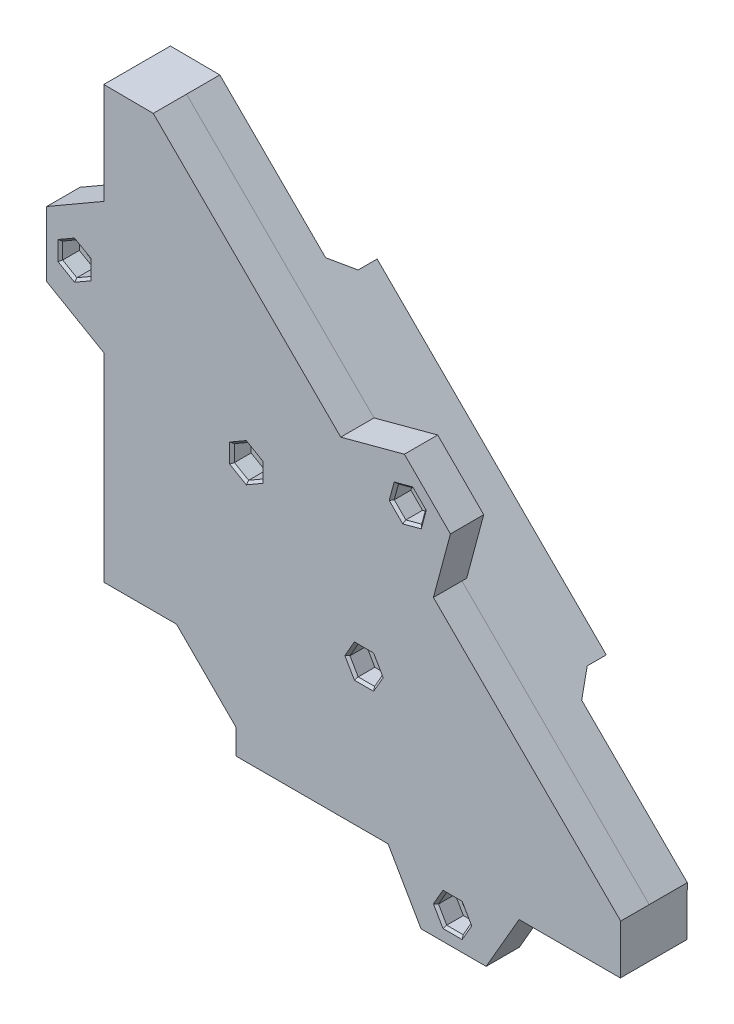
SolidWorks part; units mm, degrees
ref_plane "Front Plane" through (0, 0, 0) normal (0, 0, 1) x (1, 0, 0)
ref_plane "Top Plane" through (0, 0, 0) normal (0, 1, 0) x (1, 0, 0)
ref_plane "Right Plane" through (0, 0, 0) normal (1, 0, 0) x (0, 0, -1)
sketch "Sketch1" plane through (0, 0, 0) normal (0, 0, 1) x (1, 0, 0)
  line L0 (-86.0013, 66.2134) -> (-46.6464, 27) construction
  line L1 (-46.6464, 27) -> (-46.7159, 16.3926) construction
  line L2 (-46.7159, 16.3926) -> (-68.069, 16.3926) construction
  line L3 (-68.069, 16.3926) -> (-74.9972, 4.3926) construction
  line L4 (-74.9972, 4.3926) -> (-88.8536, 4.3926) construction
  line L5 (-88.8536, 4.3926) -> (-95.7818, 16.3926) construction
  line L6 (-95.7818, 16.3926) -> (-127.85, 16.3926) construction
  line L7 (-127.85, 16.3926) -> (-127.85, 21.7674) construction
  line L8 (-127.85, 21.7674) -> (-140.2326, 34.15) construction
  line L9 (-140.2326, 34.15) -> (-155.6074, 34.15) construction
  line L11 (-155.6074, 125.0695) -> (-145, 125) construction
  line L12 (-145, 125) -> (-105.6047, 85.7815) construction
  line L13 (-105.6047, 85.7815) -> (-92.2204, 89.3678) construction
  line L14 (-92.2204, 89.3678) -> (-82.4224, 79.5698) construction
  line L15 (-82.4224, 79.5698) -> (-86.0013, 66.2134) construction
  line L16 (-155.6074, 125.0695) -> (-155.6074, 103.716) construction
  line L17 (-155.6074, 103.716) -> (-167.6074, 96.7878) construction
  line L18 (-167.6074, 96.7878) -> (-167.6074, 82.9314) construction
  line L19 (-167.6074, 82.9314) -> (-155.6074, 76.0032) construction
  line L20 (-155.6074, 76.0032) -> (-155.6074, 34.15) construction
  line L21 (-86.1686, 66.1684) -> (-46.7969, 26.9381)
  line L22 (-46.7969, 26.9381) -> (-46.8649, 16.5426)
  line L23 (-46.8649, 16.5426) -> (-68.1556, 16.5426)
  line L24 (-68.1556, 16.5426) -> (-75.0838, 4.5426)
  line L25 (-75.0838, 4.5426) -> (-88.767, 4.5426)
  line L26 (-88.767, 4.5426) -> (-95.6952, 16.5426)
  line L27 (-95.6952, 16.5426) -> (-127.7, 16.5426)
  line L28 (-127.7, 16.5426) -> (-127.7, 21.8296)
  line L29 (-127.7, 21.8296) -> (-140.1704, 34.3)
  line L30 (-140.1704, 34.3) -> (-155.4574, 34.3)
  line L31 (-155.4574, 76.0898) -> (-155.4574, 34.3)
  line L32 (-167.4574, 83.018) -> (-155.4574, 76.0898)
  line L33 (-167.4574, 96.7012) -> (-167.4574, 83.018)
  line L34 (-155.4574, 103.6294) -> (-167.4574, 96.7012)
  line L35 (-155.4574, 124.9185) -> (-155.4574, 103.6294)
  line L36 (-155.4574, 124.9185) -> (-145.0623, 124.8504)
  line L37 (-145.0623, 124.8504) -> (-105.6493, 85.6143)
  line L38 (-105.6493, 85.6143) -> (-92.2652, 89.2005)
  line L39 (-92.2652, 89.2005) -> (-82.5897, 79.525)
  line L40 (-82.5897, 79.525) -> (-86.1686, 66.1684)
  dimension "D1" = 0.15
extrude "Boss-Extrude1" add sketch "Sketch1" against normal up to surface (7 mm away)
sketch "Sketch2" plane through (0, 0, -7) normal (0, 0, -1) x (-1, 0, 0)
  circle A0 centre (82.1404, 10.3926) radius 2.05
  circle A1 centre (91.5641, 80.2262) radius 2.05
  circle A2 centre (161.6074, 89.8596) radius 2.05
  dimension "D1" = 4.1
  dimension "D2" = 4.1
  dimension "D3" = 4.1
extrude "Cut-Extrude1" cut sketch "Sketch2" against normal through all
sketch "Sketch3" plane through (0, 0, 0) normal (0, 0, 1) x (1, 0, 0)
  line L1 (-158.6196, 88.1346) -> (-158.6196, 91.5846)
  line L2 (-158.6196, 91.5846) -> (-161.6074, 93.3096)
  line L3 (-161.6074, 93.3096) -> (-164.5951, 91.5846)
  line L4 (-164.5951, 91.5846) -> (-164.5951, 88.1346)
  line L5 (-164.5951, 88.1346) -> (-161.6074, 86.4096)
  line L6 (-161.6074, 86.4096) -> (-158.6196, 88.1346)
  line L7 (-88.2316, 81.1191) -> (-90.6711, 83.5586)
  line L8 (-90.6711, 83.5586) -> (-94.0036, 82.6657)
  line L9 (-94.0036, 82.6657) -> (-94.8965, 79.3333)
  line L10 (-94.8965, 79.3333) -> (-92.457, 76.8937)
  line L11 (-92.457, 76.8937) -> (-89.1245, 77.7867)
  line L12 (-89.1245, 77.7867) -> (-88.2316, 81.1191)
  line L13 (-80.4154, 7.4049) -> (-78.6904, 10.3926)
  line L14 (-78.6904, 10.3926) -> (-80.4154, 13.3804)
  line L15 (-80.4154, 13.3804) -> (-83.8654, 13.3804)
  line L16 (-83.8654, 13.3804) -> (-85.5904, 10.3926)
  line L17 (-85.5904, 10.3926) -> (-83.8654, 7.4049)
  line L18 (-83.8654, 7.4049) -> (-80.4154, 7.4049)
  line L19 (-167.4574, 96.7012) -> (-167.4574, 83.018) construction
  line L20 (-88.767, 4.5426) -> (-75.0838, 4.5426) construction
  line L21 (-82.5897, 79.525) -> (-92.2652, 89.2005) construction
  circle A0 centre (-161.6074, 89.8596) radius 2.9878 construction
  circle A1 centre (-91.5641, 80.2262) radius 2.9878 construction
  circle A2 centre (-82.1404, 10.3926) radius 2.9878 construction
  dimension "D1" = 6.9
  dimension "D2" = 6.9
  dimension "D3" = 6.9
extrude "Cut-Extrude2" cut sketch "Sketch3" against normal blind 4
sketch "Sketch19" plane through (0, 0, -7) normal (0, 0, -1) x (-1, 0, 0)
  line L0 (46.8649, 16.5426) -> (46.7969, 26.9381)
  line L1 (46.7969, 26.9381) -> (145.0623, 124.8504)
  line L2 (145.0623, 124.8504) -> (155.4574, 124.9185)
  line L3 (155.4574, 124.9185) -> (155.4574, 34.3)
  line L4 (155.4574, 34.3) -> (140.1704, 34.3)
  line L5 (140.1704, 34.3) -> (127.7, 21.8296)
  line L6 (127.7, 21.8296) -> (127.7, 16.5426)
  line L7 (127.7, 16.5426) -> (46.8649, 16.5426)
extrude "Boss-Extrude8" add sketch "Sketch19" along normal blind 7 and the other way blind 1
sketch "Sketch20" plane through (0, 0, -14) normal (0, 0, -1) x (-1, 0, 0)
  line L0 (114.7887, 8.9183) -> (162.872, 57.0015) construction
  line L1 (127.7, 21.8296) -> (140.1704, 34.3) construction
  line L2 (138.8303, 32.9599) -> (87.4275, 84.3628) construction
  line L3 (92.2652, 89.2005) -> (82.5897, 79.525) construction
  line L4 (114.7887, 8.9183) -> (63.1699, 60.5371) construction
  line L5 (63.1699, 60.5371) -> (111.2532, 108.6203) construction
  line L6 (111.2532, 108.6203) -> (162.872, 57.0015) construction
  line L7 (127.7, 16.5426) -> (107.1643, 16.5426)
  line L8 (46.8649, 16.5426) -> (127.7, 16.5426) construction
  line L9 (107.1643, 16.5426) -> (71.8278, 51.8791)
  line L10 (145.0623, 124.8504) -> (46.7969, 26.9381) construction
  line L11 (71.8278, 51.8791) -> (119.9977, 99.8758)
  line L12 (86.1686, 66.1684) -> (145.0623, 124.8504) construction
  line L13 (119.9977, 99.8758) -> (155.4574, 64.4161)
  line L14 (155.4574, 34.3) -> (155.4574, 124.9185) construction
  line L15 (155.4574, 64.4161) -> (155.4574, 34.3)
  line L16 (155.4574, 34.3) -> (140.1704, 34.3)
  line L17 (140.1704, 34.3) -> (127.7, 21.8296)
  line L18 (127.7, 21.8296) -> (127.7, 16.5426)
  dimension "D1" = 68
  dimension "D2" = 73
extrude "Boss-Extrude9" add sketch "Sketch20" along normal blind 8
sketch "Sketch22" plane through (0, 0, -22) normal (0, 0, -1) x (-1, 0, 0)
  circle A0 centre (100.7526, 46.2889) radius 2
  circle A1 centre (125.5014, 71.0376) radius 2
  dimension "D1" = 4
  dimension "D2" = 4
extrude "Cut-Extrude3" cut sketch "Sketch22" against normal through all
sketch "Sketch23" plane through (0, 0, 0) normal (0, 0, 1) x (1, 0, 0)
  line L1 (-125.5014, 74.4876) -> (-128.4892, 72.7626)
  line L2 (-128.4892, 72.7626) -> (-128.4892, 69.3126)
  line L3 (-128.4892, 69.3126) -> (-125.5014, 67.5876)
  line L4 (-125.5014, 67.5876) -> (-122.5136, 69.3126)
  line L5 (-122.5136, 69.3126) -> (-122.5136, 72.7626)
  line L6 (-122.5136, 72.7626) -> (-125.5014, 74.4876)
  line L7 (-104.2026, 46.2889) -> (-102.4776, 43.3011)
  line L8 (-102.4776, 43.3011) -> (-99.0276, 43.3011)
  line L9 (-99.0276, 43.3011) -> (-97.3026, 46.2889)
  line L10 (-97.3026, 46.2889) -> (-99.0276, 49.2767)
  line L11 (-99.0276, 49.2767) -> (-102.4776, 49.2767)
  line L12 (-102.4776, 49.2767) -> (-104.2026, 46.2889)
  circle A0 centre (-125.5014, 71.0376) radius 2.9878 construction
  circle A1 centre (-100.7526, 46.2889) radius 2.9878 construction
  dimension "D1" = 6.9
  dimension "D2" = 6.9
extrude "Cut-Extrude4" cut sketch "Sketch23" against normal blind 4
chamfer "Chamfer1" distance 0.5 angle 45 18 edges at (-79.5529, 8.8987, 0) (-79.5529, 11.8865, 0) (-82.1404, 13.3804, 0) (-84.7279, 11.8865, 0) (-84.7279, 8.8987, 0) (-82.1404, 7.4049, 0) (-89.4514, 82.3389, 0) (-92.3374, 83.1122, 0) (-94.45, 80.9995, 0) (-93.6767, 78.1135, 0) (-90.7908, 77.3402, 0) (-88.6781, 79.4529, 0) (-158.6196, 89.8596, 0) (-160.1135, 92.4471, 0) (-163.1013, 92.4471, 0) (-164.5951, 89.8596, 0) (-163.1013, 87.2721, 0) (-160.1135, 87.2721, 0)
chamfer "Chamfer2" distance 0.5 angle 45 12 edges at (-103.3401, 44.795, 0) (-100.7526, 43.3011, 0) (-98.1651, 44.795, 0) (-98.1651, 47.7828, 0) (-100.7526, 49.2767, 0) (-103.3401, 47.7828, 0) (-126.9953, 73.6251, 0) (-128.4892, 71.0376, 0) (-126.9953, 68.4501, 0) (-124.0075, 68.4501, 0) (-122.5136, 71.0376, 0) (-124.0075, 73.6251, 0)
chamfer "Chamfer3" distance 4 angle 45 2 edges at (-89.4961, 34.2109, -14) (-137.7275, 82.146, -14)
